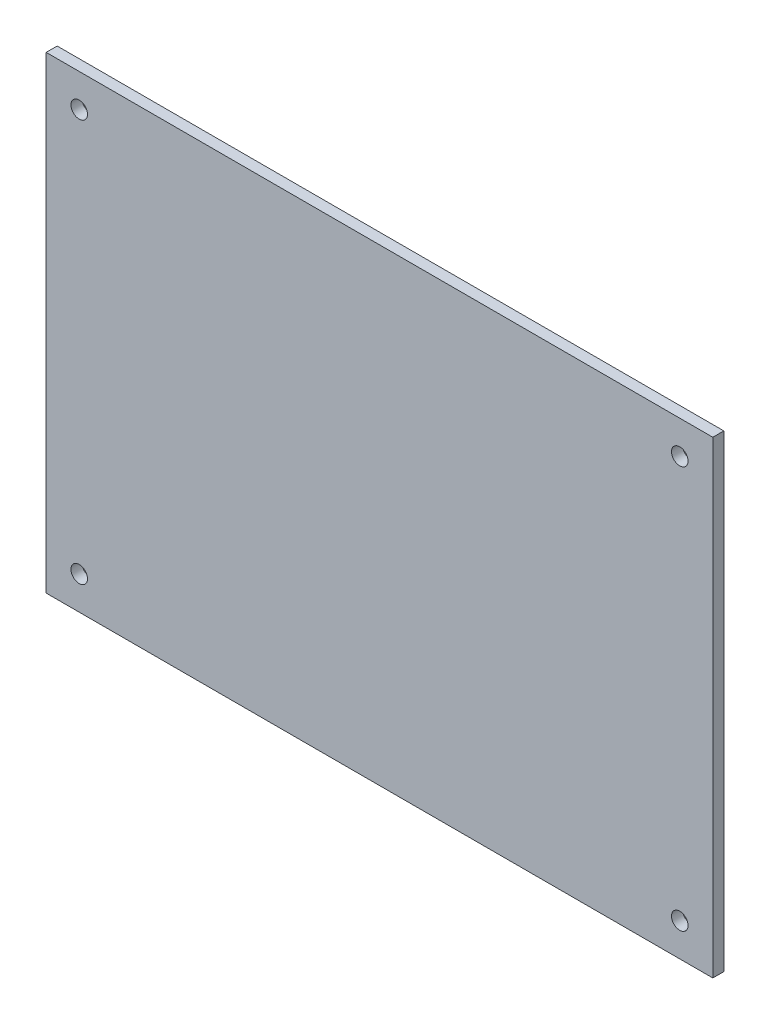
SolidWorks part; units mm, degrees
ref_plane "Ön Düzlem" through (0, 0, 0) normal (0, 0, 1) x (1, 0, 0)
ref_plane "Üst Düzlem" through (0, 0, 0) normal (0, 1, 0) x (1, 0, 0)
ref_plane "Sağ Düzlem" through (0, 0, 0) normal (1, 0, 0) x (0, 0, -1)
sketch "Sketch1" plane through (0, 0, 0) normal (0, 0, 1) x (1, 0, 0)
  line L1 (0, 0) -> (121, 0)
  line L2 (0, 0) -> (0, 85)
  line L3 (0, 85) -> (121, 85)
  line L4 (121, 0) -> (121, 85)
extrude "Boss-Extrude1" add sketch "Sketch1" along normal blind 2
sketch "Sketch4" plane through (0, 0, 2) normal (0, 0, 1) x (1, 0, 0)
  line L0 (0, 85) -> (0, 0) construction
  line L1 (10, 10) -> (111, 10) construction
  line L2 (10, 10) -> (10, 75) construction
  line L3 (10, 75) -> (111, 75) construction
  line L4 (111, 10) -> (111, 75) construction
  line L5 (0, 0) -> (121, 0) construction
  dimension "D1" = 10
  dimension "D2" = 10
sketch "Sketch5" plane through (0, 0, 2) normal (0, 0, 1) x (1, 0, 0)
  line L0 (0, 85) -> (0, 0) construction
  line L1 (121, 85) -> (0, 85) construction
  line L2 (121, 0) -> (121, 85) construction
  line L3 (0, 0) -> (121, 0) construction
  circle A0 centre (6, 79) radius 1.5
  circle A1 centre (115, 79) radius 1.5
  circle A2 centre (6, 6) radius 1.5
  circle A3 centre (115, 6) radius 1.5
  dimension "D1" = 6
  dimension "D3" = 6
  dimension "D5" = 6
  dimension "D2" = 6
  dimension "D4" = 6
extrude "Cut-Extrude2" cut sketch "Sketch5" against normal through all
